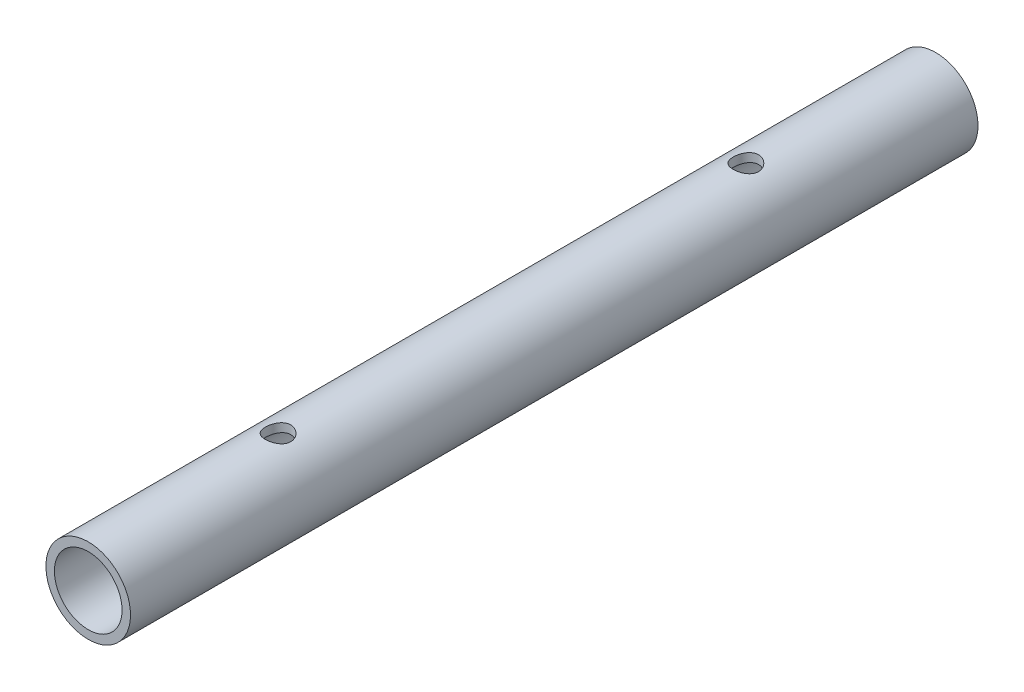
SolidWorks part; units mm, degrees
ref_plane "Plan de face" through (0, 0, 0) normal (0, 0, 1) x (1, 0, 0)
ref_plane "Plan de dessus" through (0, 0, 0) normal (0, 1, 0) x (1, 0, 0)
ref_plane "Plan de droite" through (0, 0, 0) normal (1, 0, 0) x (0, 0, -1)
sketch "Sketch1" plane through (0, 0, 0) normal (0, 0, 1) x (1, 0, 0)
  circle A0 centre (0, 0) radius 5
extrude "Boss-Extrude1" add sketch "Sketch1" along normal blind 100.19
sketch "Sketch2" plane through (0, 0, 100.19) normal (0, 0, 1) x (1, 0, 0)
  circle A0 centre (0, 0) radius 4
extrude "Cut-Extrude1" cut sketch "Sketch2" against normal up to next
sketch "Sketch5" plane through (0, 0, 0) normal (0, 1, 0) x (1, 0, 0)
  circle A0 centre (0, -22.443) radius 1.5
  circle A1 centre (0, -77.748) radius 1.5
  dimension "D1" = 22.443
  dimension "D2" = 77.748
extrude "Cut-Extrude2" cut sketch "Sketch5" against normal through all and the other way through all
